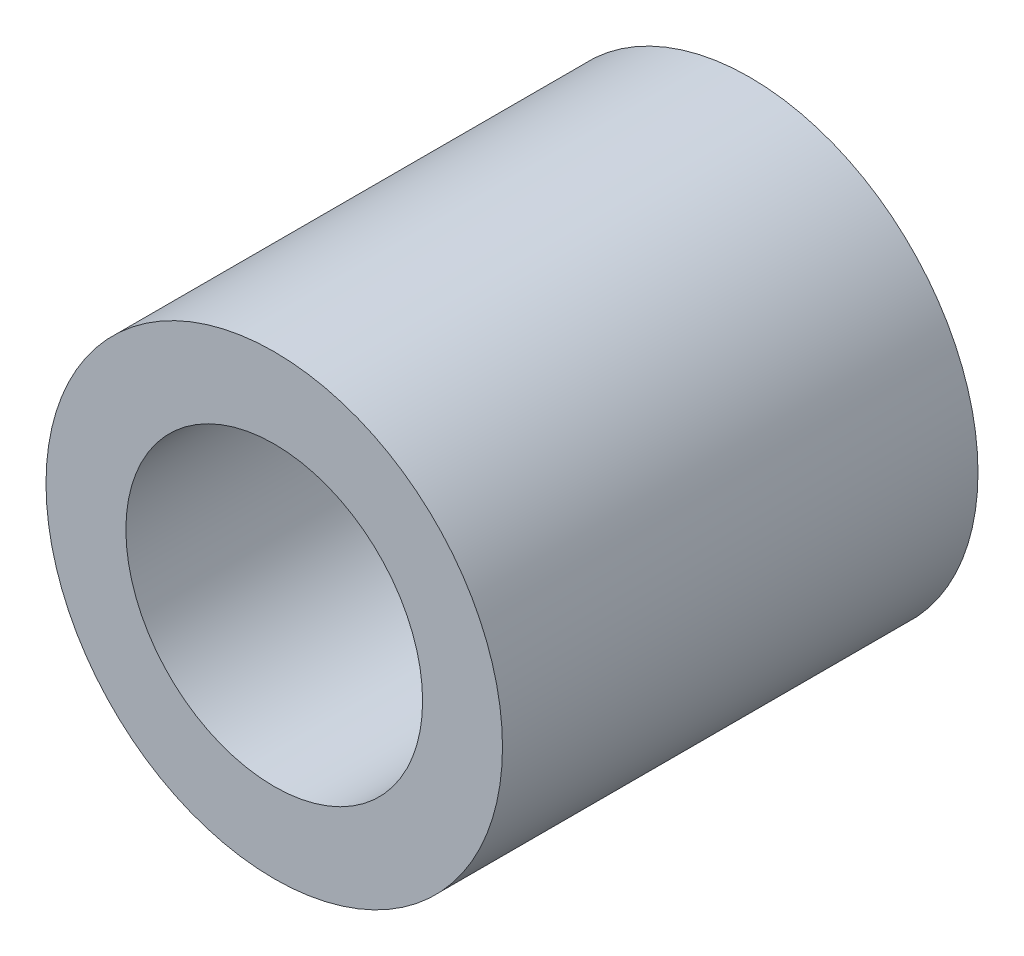
SolidWorks part; units mm, degrees
ref_plane "Front" through (0, 0, 0) normal (0, 0, 1) x (1, 0, 0)
ref_plane "Top" through (0, 0, 0) normal (0, 1, 0) x (1, 0, 0)
ref_plane "Right" through (0, 0, 0) normal (1, 0, 0) x (0, 0, -1)
sketch "Sketch1" plane through (0, 0, 0) normal (0, 0, 1) x (1, 0, 0)
  circle A0 centre (0, 0) radius 6.9342
  circle A2 centre (0, 0) radius 10.668
  dimension "D1" = 13.8684
  dimension "D2" = 21.336
extrude "Boss-Extrude1" add sketch "Sketch1" along normal blind 22.225
